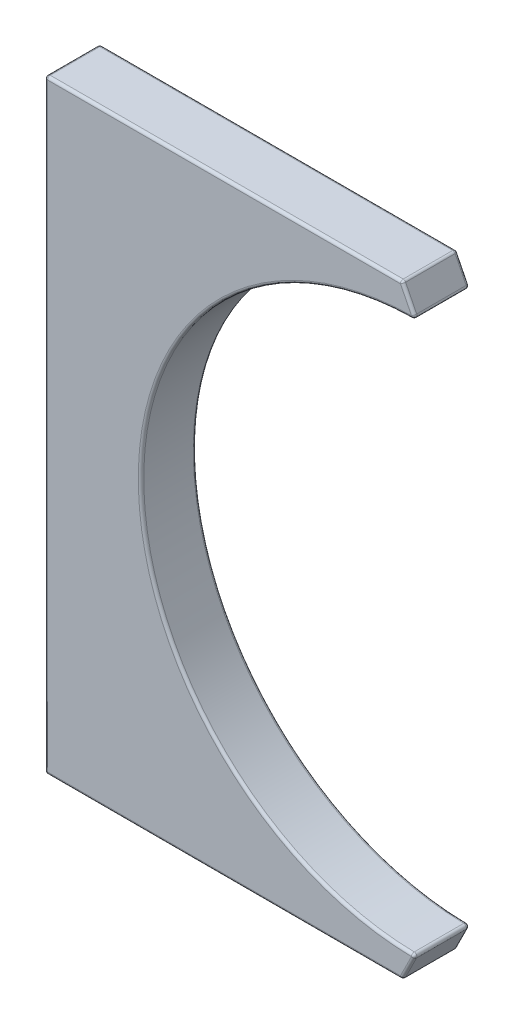
SolidWorks part; units mm, degrees
ref_plane "Front Plane" through (0, 0, 0) normal (0, 0, 1) x (1, 0, 0)
ref_plane "Top Plane" through (0, 0, 0) normal (0, 1, 0) x (1, 0, 0)
ref_plane "Right Plane" through (0, 0, 0) normal (1, 0, 0) x (0, 0, -1)
sketch "Sketch2" plane through (0, 0, 0) normal (0, 0, 1) x (1, 0, 0)
  line L0 (0, 105.3519) -> (0, -114.6481)
  line L1 (0, -114.6481) -> (130, -114.6481)
  line L2 (130, -114.6481) -> (135, -104.6481)
  line L3 (0, 105.3519) -> (130, 105.3519)
  line L4 (130, 105.3519) -> (135, 95.3519)
  arc A0 (135, 95.3519) -> (135, -104.6481) centre (135, -4.6481) ccw
  dimension "D1" = 200
  dimension "D2" = 135
  dimension "D3" = 130
  dimension "D4" = 110
  dimension "D5" = 220
  dimension "D6" = 130
extrude "Boss-Extrude1" add sketch "Sketch2" along normal blind 20
fillet "Fillet1" radius 1 18 edges at (0, -114.6481, 10) (130, -114.6481, 10) (0, -4.6481, 0) (65, -114.6481, 0) (132.5, -109.6481, 0) (132.5, 100.3519, 0) (135, -104.6481, 10) (135, 95.3519, 10) (35, -4.6481, 0) (132.5, 100.3519, 20) (35, -4.6481, 20) (132.5, -109.6481, 20) (65, -114.6481, 20) (0, -4.6481, 20) (130, 105.3519, 10) (65, 105.3519, 20) (0, 105.3519, 10) (65, 105.3519, 0)
